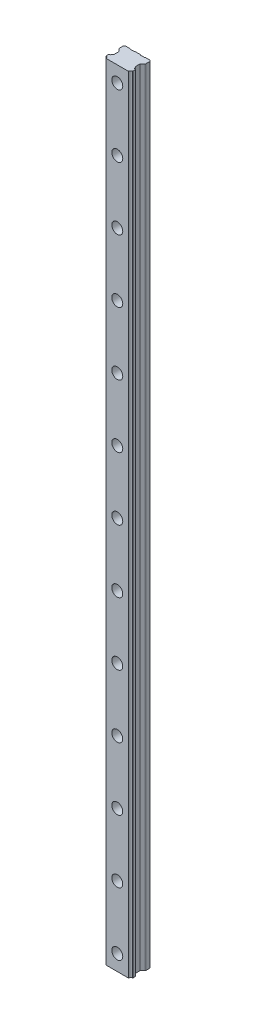
SolidWorks part; units mm, degrees
ref_plane "Front" through (0, 0, 0) normal (0, 0, 1) x (1, 0, 0)
ref_plane "Top" through (0, 0, 0) normal (0, 1, 0) x (1, 0, 0)
ref_plane "Right" through (0, 0, 0) normal (1, 0, 0) x (0, 0, -1)
sketch "Sketch1" plane through (0, 0, 0) normal (0, 1, 0) x (1, 0, 0)
  line L0 (17, 5.9313) -> (17, 3.0688)
  line L1 (13.796, 9.3071) -> (14.2395, 8.8636)
  line L2 (13.5, 15.0814) -> (13.5, 10.0142)
  line L3 (16.7071, 18.7071) -> (13.796, 15.796)
  line L4 (17, 24.5) -> (17, 19.4142)
  line L5 (15.5, 26) -> (17, 24.5)
  line L6 (9.5, 26) -> (15.5, 26)
  line L7 (9.1465, 25.6465) -> (9.5, 26)
  line L8 (4.2034, 25.5) -> (8.7929, 25.5)
  line L9 (3.5, 26) -> (3.8535, 25.6465)
  line L10 (3.5, 26) -> (-3.5, 26)
  line L11 (-3.5, 26) -> (-3.8535, 25.6465)
  line L12 (-4.2034, 25.5) -> (-8.7929, 25.5)
  line L13 (-9.1465, 25.6465) -> (-9.5, 26)
  line L14 (-9.5, 26) -> (-15.5, 26)
  line L15 (-15.5, 26) -> (-17, 24.5)
  line L16 (-17, 24.5) -> (-17, 19.4142)
  line L17 (-16.7071, 18.7071) -> (-13.796, 15.796)
  line L18 (-13.5, 15.0814) -> (-13.5, 10.0142)
  line L19 (-13.796, 9.3071) -> (-14.2395, 8.8636)
  line L20 (-17, 5.9313) -> (-17, 3.0688)
  line L21 (14.0245, 0) -> (-14.0245, 0)
  line L22 (0, -3.99) -> (0, 28.5092) construction
  arc A0 (14.3203, 0.2642) -> (14.0245, 0) centre (14.0245, 0.2977) cw
  arc A1 (14.3203, 0.2642) -> (16.748, 2.7711) centre (17.1614, -0.0583) cw
  arc A2 (17, 3.0688) -> (16.748, 2.7711) centre (16.6981, 3.0688) cw
  arc A3 (16.748, 6.2271) -> (17, 5.9313) centre (16.7055, 5.9357) cw
  arc A4 (16.748, 6.2271) -> (14.3248, 8.69) centre (17.1606, 9.0566) cw
  arc A5 (14.2395, 8.8636) -> (14.3248, 8.69) centre (14.0273, 8.6515) cw
  arc A6 (13.796, 9.3071) -> (13.5, 10.0142) centre (14.4531, 9.9977) cw
  arc A7 (13.5, 15.0814) -> (13.796, 15.796) centre (14.5106, 15.0814) cw
  arc A8 (17, 19.4142) -> (16.7071, 18.7071) centre (16, 19.4142) cw
  arc A9 (9.1465, 25.6465) -> (8.7929, 25.5) centre (8.7929, 26) cw
  arc A10 (-4.2034, 25.5) -> (-3.8535, 25.6465) centre (-4.2034, 25.991) ccw
  arc A11 (-9.1465, 25.6465) -> (-8.7929, 25.5) centre (-8.7929, 26) ccw
  arc A12 (-17, 19.4142) -> (-16.7071, 18.7071) centre (-16, 19.4142) ccw
  arc A13 (-13.5, 15.0814) -> (-13.796, 15.796) centre (-14.5106, 15.0814) ccw
  arc A14 (-13.796, 9.3071) -> (-13.5, 10.0142) centre (-14.4531, 9.9977) ccw
  arc A15 (-14.2395, 8.8636) -> (-14.3248, 8.69) centre (-14.0273, 8.6515) ccw
  arc A16 (-16.748, 6.2271) -> (-14.3248, 8.69) centre (-17.1606, 9.0566) ccw
  arc A17 (-16.748, 6.2271) -> (-17, 5.9313) centre (-16.7055, 5.9357) ccw
  arc A18 (-17, 3.0688) -> (-16.748, 2.7711) centre (-16.6981, 3.0688) ccw
  arc A19 (-14.3203, 0.2642) -> (-16.748, 2.7711) centre (-17.1614, -0.0583) ccw
  arc A20 (-14.3203, 0.2642) -> (-14.0245, 0) centre (-14.0245, 0.2977) ccw
  arc A21 (4.2034, 25.5) -> (3.8535, 25.6465) centre (4.2034, 25.991) cw
  dimension "D1" = 34
  dimension "D2" = 26
  dimension "D3" = 27
  dimension "D4" = 25.5
  dimension "D5" = 0.491
  dimension "D6" = 1.5
  dimension "D7" = 28.0489
  dimension "D8" = 0.2977
  dimension "D9" = 0.3019
  dimension "D10" = 1
  dimension "D11" = 1.0106
  dimension "D12" = 3.5
extrude "Boss-Extrude1" add sketch "Sketch1" along normal blind 1000
hole_wizard "CBORE for M8 Socket Head Cap Screw1" positions "Sketch3" profile "Sketch2" counterbore size "M8" standard "JIS" end condition through all
sketch "Sketch3" plane through (0, 0, 0) normal (0, 0, 1) x (1, 0, 0)
  line L0 (-14.0245, 0) -> (14.0245, 0) construction
  point P0 (0, 20)
  dimension "D1" = 20
sketch "Sketch2" plane through (0, 20, 0) normal (1, 0, 0) x (0, -1, 0)
  line L0 (0, 0) -> (0, 26)
  line L1 (0, 26) -> (4.5, 26)
  line L3 (4.5, 26) -> (4.5, 12)
  line L4 (4.5, 12) -> (7, 12)
  line L5 (7, 12) -> (7, 0)
  line L7 (7, 0) -> (0, 0)
  line L11 (0, -6.35) -> (0, 107.95) construction
  dimension "Thru Hole Dia." = 9
  dimension "Thru Hole Depth" = 26
  dimension "C'Bore Dia." = 14
  dimension "C'Bore Depth" = 12
pattern_linear "LPattern1" count 13 spacing 80 along (0, 1, 0) of "CBORE for M8 Socket Head Cap Screw1"
